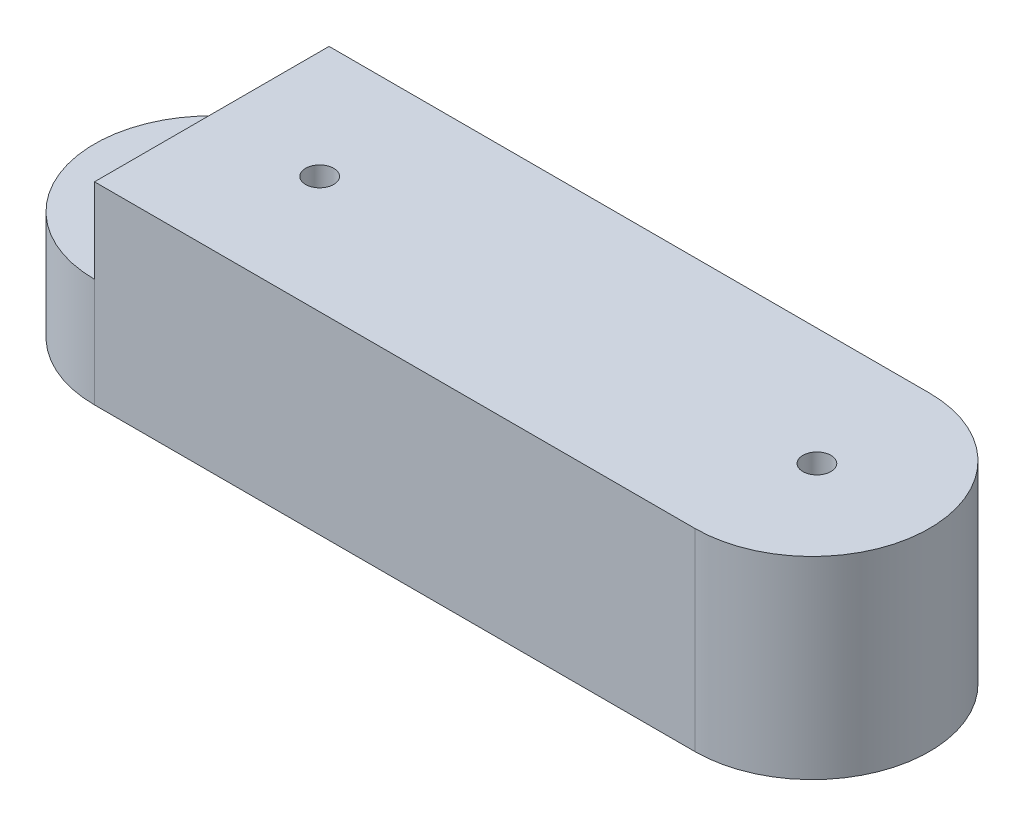
SolidWorks part; units mm, degrees
material "Alloy Steel"
ref_plane "Front Plane" through (0, 0, 0) normal (0, 0, 1) x (1, 0, 0)
ref_plane "Top Plane" through (0, 0, 0) normal (0, 1, 0) x (1, 0, 0)
ref_plane "Right Plane" through (0, 0, 0) normal (1, 0, 0) x (0, 0, -1)
sketch "Sketch1" plane through (0, 0, 0) normal (0, 1, 0) x (1, 0, 0)
  line L1 (0, 0) -> (64, 0)
  line L2 (0, 0) -> (0, 25)
  line L3 (0, 25) -> (64, 25)
  line L4 (64, 0) -> (64, 25)
  circle A0 centre (0, 12.5) radius 12.5
  circle A1 centre (64, 12.5) radius 12.5
  dimension "D2" = 64
  dimension "D1" = 25
extrude "Boss-Extrude1" add sketch "Sketch1" along normal blind 20.6 contours L2 A0 | L2 A0 | A1 L3 A0 L1 | L4 A1 | L4 A1
sketch "Sketch3" plane through (0, 20.6, 0) normal (0, 1, 0) x (1, 0, 0)
  line L0 (0, 0) -> (0, 25)
  circle A0 centre (0, 12.5) radius 12.5
  arc M1 (0, 25) -> (0, 0) centre (0, 12.5) ccw
  dimension "D1" = 25
extrude "Cut-Extrude1" cut sketch "Sketch3" against normal blind 9 contours L0 M1
sketch "Sketch4" plane through (0, 20.6, 0) normal (0, 1, 0) x (1, 0, 0)
  line L0 (0, 25) -> (64, 25) construction
  circle A0 centre (64.5, 12.5) radius 1.5
  circle A1 centre (11.5, 12.5) radius 1.5
  arc A2 (64, 0) -> (64, 25) centre (64, 12.5) ccw construction
  point P9 (76.5, 12.5)
  dimension "D1" = 3
  dimension "D3" = 12
  dimension "D4" = 12.5
  dimension "D5" = 53
  dimension "D2" = 12.5
extrude "Cut-Extrude2" cut sketch "Sketch4" against normal blind 4
